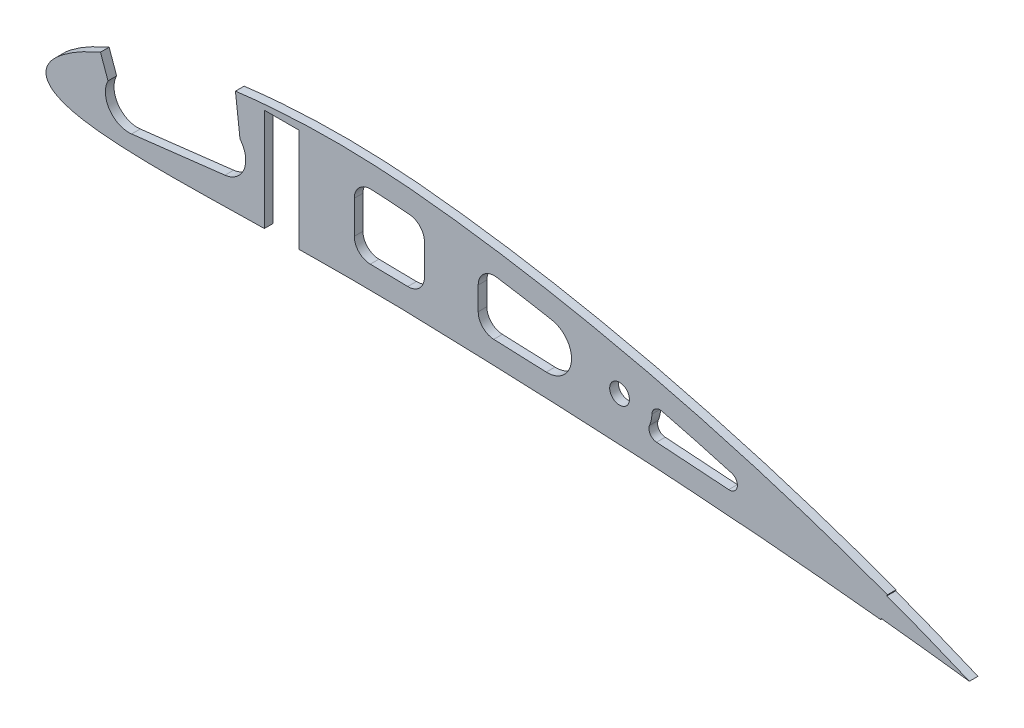
SolidWorks part; units mm, degrees
ref_plane "Front Plane" through (0, 0, 0) normal (0, 0, 1) x (1, 0, 0)
ref_plane "Top Plane" through (0, 0, 0) normal (0, 1, 0) x (1, 0, 0)
ref_plane "Right Plane" through (0, 0, 0) normal (1, 0, 0) x (0, 0, -1)
sketch "Sketch1" plane through (0, 0, 0) normal (0, 0, 1) x (1, 0, 0)
  line L0 (2483.024, 2922.8796) -> (2519.7776, 2927.2095)
  line L1 (2535.2748, 2957.1172) -> (2535.2748, 2916.7673)
  line L2 (2548.8638, 2957.1172) -> (2535.2748, 2957.1172)
  line L3 (2548.8638, 2957.1172) -> (2548.8638, 2917.0124)
  line L4 (2473.7279, 2936.3266) -> (2470.7661, 2944.6344)
  line L5 (2525.6942, 2942.4487) -> (2523.8959, 2957.9177)
  line L6 (2548.8638, 2917.0124) -> (2548.8703, 2916.492)
  line L7 (2570.6824, 2944.7947) -> (2570.6824, 2931.8276)
  line L8 (2619.4631, 2939.6017) -> (2619.4631, 2930.4973)
  line L9 (2598.2795, 2943.8024) -> (2598.2795, 2931.5864)
  line L10 (2780.3662, 2914.0559) -> (2780.5427, 2914.5293)
  line L11 (2778.0193, 2905.2682) -> (2777.9678, 2904.7443)
  arc A0 (2519.7776, 2927.2095) -> (2525.6942, 2942.4487) centre (2518.6951, 2936.3979) ccw
  arc A1 (2473.7279, 2936.3266) -> (2483.024, 2922.8796) centre (2481.9415, 2932.068) ccw
  circle A2 centre (2675.1058, 2930.3661) radius 3.8862
  arc A3 (2646.2636, 2923.3273) -> (2648.4261, 2942.2073) centre (2646.6833, 2932.8431) ccw
  arc A4 (2577.3176, 2951.1383) -> (2570.6824, 2944.7947) centre (2577.0324, 2944.7947) ccw
  arc A5 (2570.6824, 2931.8276) -> (2576.9704, 2925.4779) centre (2577.0324, 2931.8276) ccw
  arc A6 (2591.7408, 2925.2392) -> (2598.2795, 2931.5864) centre (2591.9295, 2931.5864) ccw
  arc A7 (2598.2795, 2943.8024) -> (2592.4959, 2950.1271) centre (2591.9295, 2943.8024) ccw
  arc A8 (2626.7739, 2945.8786) -> (2619.4631, 2939.6017) centre (2625.8131, 2939.6017) ccw
  arc A9 (2619.4631, 2930.4973) -> (2625.5704, 2924.152) centre (2625.8131, 2930.4973) ccw
  arc A10 (2686.9168, 2925.4944) -> (2687.8696, 2929.8034) centre (2675.1058, 2930.3661) ccw
  arc A11 (2691.8173, 2932.7424) -> (2687.8696, 2929.8034) centre (2691.0416, 2929.6636) ccw
  arc A12 (2686.9168, 2925.4944) -> (2689.6687, 2921.114) centre (2689.8519, 2924.2837) ccw
  arc A13 (2718.0983, 2919.1727) -> (2719.2039, 2925.3917) centre (2718.3306, 2922.3392) ccw
  spline S0 degree 3 poles (2548.8703, 2916.492) (2549.8808, 2916.5047) (2552.5653, 2916.54) (2556.9478, 2916.6008) (2562.0305, 2916.6026) (2567.1738, 2916.6177) (2572.378, 2916.6334) (2577.6546, 2916.6012) (2582.9782, 2916.5063) (2588.3501, 2916.4604) (2593.7796, 2916.2755) (2599.3074, 2916.1214) (2604.9087, 2915.9429) (2610.5722, 2915.7907) (2616.2572, 2915.5462) (2621.9699, 2915.4008) (2627.6798, 2915.1699) (2633.4021, 2914.9578) (2639.1368, 2914.7538) (2644.8687, 2914.4893) (2650.5883, 2914.2371) (2656.2963, 2914.0049) (2661.9877, 2913.6836) (2667.6718, 2913.4799) (2673.3112, 2913.1273) (2678.9152, 2912.8192) (2684.4815, 2912.4997) (2690.0115, 2912.1974) (2695.4894, 2911.8519) (2700.9022, 2911.4633) (2706.2541, 2911.0924) (2711.544, 2910.7193) (2716.7484, 2910.3644) (2721.8762, 2909.9736) (2726.912, 2909.5199) (2731.8817, 2909.1658) (2736.7578, 2908.729) (2741.5391, 2908.3398) (2746.2156, 2907.8858) (2750.7708, 2907.4604) (2755.2146, 2907.038) (2759.5346, 2906.6194) (2763.7464, 2906.2326) (2767.8261, 2905.767) (2771.7933, 2905.4129) (2775.1515, 2905.0168) (2777.2, 2904.8198) (2777.9678, 2904.7443) knots 19.396956 19.396956 19.396956 19.396956 19.516306 19.714059 19.914611 20.11662 20.32154 20.529276 20.739841 20.950405 21.163745 21.381461 21.603554 21.825647 22.050605 22.275616 22.500574 22.725533 22.95195 23.178326 23.403242 23.628157 23.85304 24.076496 24.299895 24.520375 24.739394 24.958414 25.174499 25.387659 25.599359 25.808139 26.013999 26.215484 26.415525 26.611171 26.803913 26.993735 27.177747 27.35884 27.534095 27.704971 27.871469 28.033634 28.189916 28.341868 28.432981 28.432981 28.432981 28.432981
  spline S1 degree 3 poles (2780.5427, 2914.5293) (2778.253, 2915.3832) (2775.9733, 2916.2525) (2770.711, 2918.1355) (2767.7251, 2919.1876) (2758.7488, 2922.3768) (2752.6839, 2924.3642) (2740.5388, 2928.2816) (2734.4556, 2930.2026) (2722.2133, 2933.804) (2716.0661, 2935.5221) (2703.7593, 2938.9198) (2697.5661, 2940.4594) (2685.1978, 2943.581) (2678.9801, 2944.965) (2659.2455, 2949.3052) (2645.7434, 2951.8789) (2623.3857, 2955.4286) (2614.7201, 2956.6523) (2599.842, 2958.3639) (2593.7119, 2959.0296) (2581.3916, 2959.8824) (2575.2189, 2960.1753) (2562.8836, 2960.4312) (2556.7118, 2960.3668) (2544.3747, 2959.8617) (2538.2135, 2959.4618) (2529.344, 2958.5812) (2526.6172, 2958.2703) (2523.8959, 2957.9177) knots 1.615896 1.615896 1.615896 1.615896 1.904436 1.904436 2.277217 2.277217 3.031526 3.031526 3.785836 3.785836 4.540146 4.540146 5.294456 5.294456 6.048766 6.048766 7.680004 7.680004 8.718619 8.718619 9.449269 9.449269 10.17992 10.17992 10.910571 10.910571 11.641222 11.641222 11.966163 11.966163 11.966163 11.966163
  spline S2 degree 3 poles (2470.7661, 2944.6344) (2470.6464, 2944.5823) (2470.5267, 2944.53) (2466.9137, 2942.9439) (2463.4641, 2941.2685) (2457.8844, 2937.8398) (2455.6089, 2936.2464) (2451.9641, 2932.8995) (2450.4657, 2931.1716) (2449.2892, 2927.9649) (2449.1568, 2926.664) (2449.952, 2924.2883) (2450.8099, 2923.239) (2452.68, 2921.7567) (2453.701, 2921.1991) (2455.7378, 2920.26) (2456.8244, 2919.8893) (2460.2041, 2918.8316) (2462.5683, 2918.3716) (2467.3207, 2917.5961) (2469.7198, 2917.3303) (2476.9483, 2916.6888) (2481.785, 2916.4354) (2491.4695, 2916.2054) (2496.312, 2916.1942) (2511.0794, 2916.2781) (2520.9791, 2916.5085) (2532.35, 2916.7113) (2533.8124, 2916.739) (2535.2748, 2916.7673) knots 14.135709 14.135709 14.135709 14.135709 14.151211 14.151211 14.604184 14.604184 14.932416 14.932416 15.199765 15.199765 15.362932 15.362932 15.5261 15.5261 15.66286 15.66286 15.79962 15.79962 16.086125 16.086125 16.37263 16.37263 16.945639 16.945639 17.518648 17.518648 18.689255 18.689255 18.862005 18.862005 18.862005 18.862005
  spline S3 degree 3 poles (2576.9704, 2925.4779) (2578.946, 2925.4586) (2580.9083, 2925.4336) (2585.7078, 2925.3681) (2588.7857, 2925.3271) (2591.7408, 2925.2392) knots 20.499375 20.499375 20.499375 20.499375 20.729095 20.729095 21.07413 21.07413 21.07413 21.07413
  spline S4 degree 3 poles (2625.5704, 2924.152) (2627.902, 2924.0628) (2630.1924, 2923.9727) (2637.0527, 2923.7211) (2641.7061, 2923.5283) (2646.2636, 2923.3273) knots 22.403986 22.403986 22.403986 22.403986 22.677701 22.677701 23.217184 23.217184 23.217184 23.217184
  spline S5 degree 3 poles (2648.4261, 2942.2073) (2641.5924, 2943.4791) (2634.7338, 2944.6473) (2627.4895, 2945.7687) (2627.1316, 2945.8238) (2626.7739, 2945.8786) knots 6.961493 6.961493 6.961493 6.961493 7.794516 7.794516 7.837818 7.837818 7.837818 7.837818
  spline S6 degree 3 poles (2592.4959, 2950.1271) (2589.2645, 2950.4165) (2586.039, 2950.6617) (2580.9583, 2950.9612) (2579.1372, 2951.0565) (2577.3176, 2951.1383) knots 9.222324 9.222324 9.222324 9.222324 9.617156 9.617156 9.837956 9.837956 9.837956 9.837956
  spline S7 degree 3 poles (2689.6687, 2921.114) (2690.9236, 2921.0415) (2692.183, 2920.9664) (2699.0659, 2920.5308) (2704.6007, 2920.1185) (2712.7745, 2919.5464) (2715.4243, 2919.3689) (2718.0983, 2919.1727) knots 24.92366 24.92366 24.92366 24.92366 25.070609 25.070609 25.727122 25.727122 26.039952 26.039952 26.039952 26.039952
  spline S8 degree 3 poles (2719.2039, 2925.3917) (2714.2381, 2926.8123) (2709.2315, 2928.2153) (2700.185, 2930.6323) (2696.0201, 2931.6835) (2691.8173, 2932.7424) knots 4.06038 4.06038 4.06038 4.06038 4.675696 4.675696 5.188469 5.188469 5.188469 5.188469
  spline S9 degree 3 poles (2812.8112, 2901.1729) (2811.7427, 2901.6198) (2810.661, 2902.0653) (2805.162, 2904.3462) (2800.7468, 2906.1339) (2791.811, 2909.7551) (2787.3909, 2911.4507) (2782.0553, 2913.4291) (2781.2108, 2913.7426) (2780.3662, 2914.0559) knots 0.240373 0.240373 0.240373 0.240373 0.376825 0.376825 0.943228 0.943228 1.509632 1.509632 1.616177 1.616177 1.616177 1.616177
  spline S10 degree 3 poles (2778.0193, 2905.2682) (2779.1748, 2905.1412) (2780.3303, 2905.0117) (2787.9969, 2904.1341) (2794.5403, 2903.4251) (2804.9356, 2902.1458) (2808.8293, 2901.6259) (2812.8112, 2901.1729) knots 28.432747 28.432747 28.432747 28.432747 28.56999 28.56999 29.343341 29.343341 29.813814 29.813814 29.813814 29.813814
extrude "Boss-Extrude1" add sketch "Sketch1" along normal blind 3.4036
